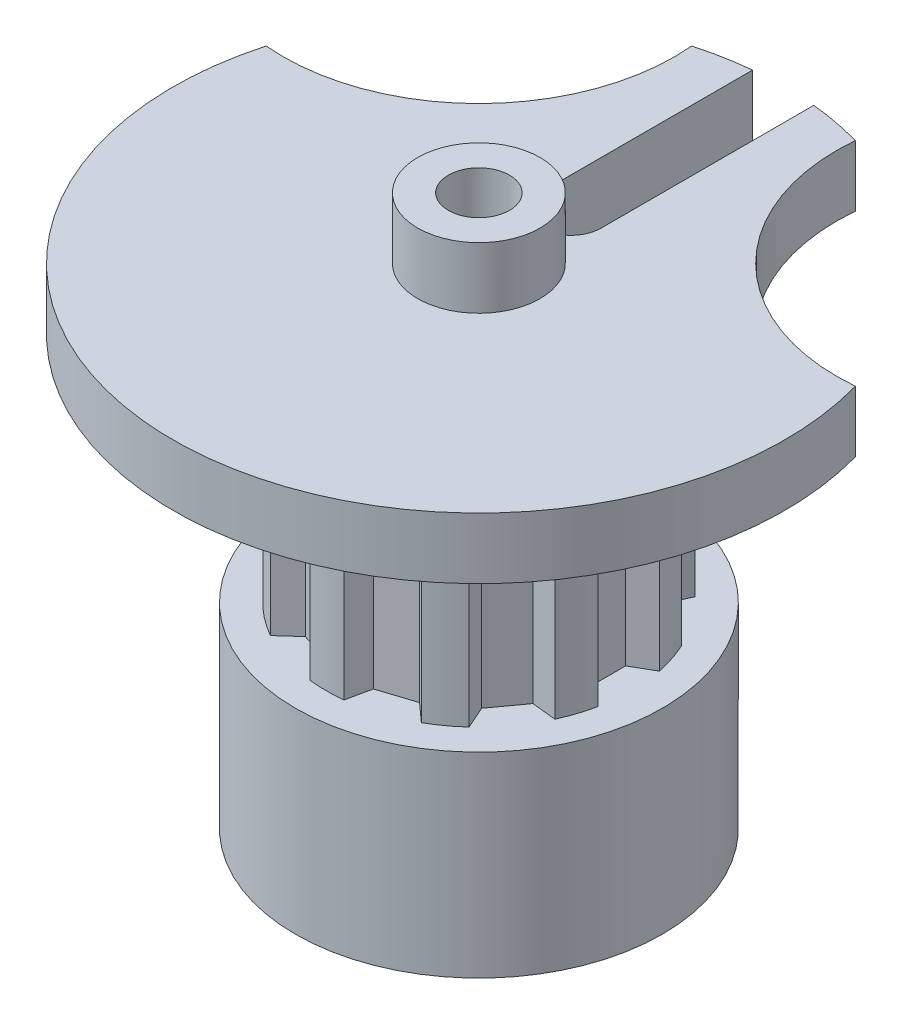
SolidWorks part; units mm, degrees
material "AISI 304"
ref_plane "Front" through (0, 0, 0) normal (0, 0, 1) x (1, 0, 0)
ref_plane "Top" through (0, 0, 0) normal (0, 1, 0) x (1, 0, 0)
ref_plane "Right" through (0, 0, 0) normal (1, 0, 0) x (0, 0, -1)
sketch "Sketch1" plane through (0, 0, 0) normal (0, 1, 0) x (1, 0, 0)
  circle A0 centre (0, 0) radius 25
  circle A1 centre (0, 0) radius 2.5
  dimension "D1" = 50
  dimension "D2" = 5
extrude "Boss-Extrude1" add sketch "Sketch1" along normal blind 5
sketch "Sketch2" plane through (0, 5, 0) normal (0, 1, 0) x (1, 0, 0)
  line L0 (-2.5, 24.8747) -> (-2.5, 7.5)
  line L1 (2.5, 7.5) -> (2.5, 24.8747)
  line L2 (-22.6274, 22.6274) -> (22.6274, 22.6274) construction
  line L3 (22.6274, 22.6274) -> (0, 0) construction
  line L4 (0, 0) -> (0, 22.6274) construction
  circle A2 centre (0, 0) radius 25 construction
  arc A3 (-2.5, 7.5) -> (2.5, 7.5) centre (0, 7.5) ccw
  circle A5 centre (22.6274, 22.6274) radius 16
  circle A6 centre (-22.6274, 22.6274) radius 16
  arc A7 (-2.5, 24.8747) -> (2.5, 24.8747) centre (0, 0) cw
  dimension "D3" = 45
  dimension "D2" = 32
  dimension "D1" = 5
  dimension "D4" = 7.5
  dimension "D5" = 32
extrude "Cut-Extrude1" cut sketch "Sketch2" against normal through all
sketch "Sketch3" plane through (0, 5, 0) normal (0, 1, 0) x (1, 0, 0)
  circle A0 centre (0, 0) radius 5
  circle A1 centre (0, 0) radius 2.5
  circle A2 centre (0, 0) radius 2.5 construction
  arc A3 (-2.5, 7.5) -> (2.5, 7.5) centre (0, 7.5) ccw construction
extrude "Boss-Extrude2" add sketch "Sketch3" along normal blind 5
sketch "Sketch4" plane through (0, 0, 0) normal (0, -1, 0) x (1, 0, 0)
  circle A0 centre (0, 0) radius 15
  circle A1 centre (0, 0) radius 2.5
  circle A2 centre (0, 0) radius 2.5 construction
  dimension "D1" = 30
extrude "Boss-Extrude3" add sketch "Sketch4" along normal blind 35
sketch "Sketch5" plane through (0, 0, 0) normal (0, 1, 0) x (1, 0, 0)
  line L33 (-10.5, 1.5) -> (-10.5, -1.5)
  line L34 (-10.5, -1.5) -> (-12.2458, -2.508)
  line L35 (-10.5, 1.5) -> (-12.2458, 2.508)
  line L36 (-7.613, 7.3853) -> (-9.3764, 4.9582)
  line L37 (-7.613, 7.3853) -> (-8.4329, 9.2269)
  line L38 (-9.3764, 4.9582) -> (-11.3812, 5.1689)
  line L39 (-1.8181, 10.4496) -> (-4.6713, 9.5226)
  line L40 (-1.8181, 10.4496) -> (-1.399, 12.4215)
  line L41 (-4.6713, 9.5226) -> (-6.1694, 10.8715)
  line L42 (4.6713, 9.5226) -> (1.8181, 10.4496)
  line L43 (4.6713, 9.5226) -> (6.1694, 10.8715)
  line L44 (1.8181, 10.4496) -> (1.399, 12.4215)
  line L45 (9.3764, 4.9582) -> (7.613, 7.3853)
  line L46 (9.3764, 4.9582) -> (11.3812, 5.1689)
  line L47 (7.613, 7.3853) -> (8.4329, 9.2269)
  line L48 (10.5, -1.5) -> (10.5, 1.5)
  line L49 (10.5, -1.5) -> (12.2458, -2.508)
  line L50 (10.5, 1.5) -> (12.2458, 2.508)
  line L51 (7.613, -7.3853) -> (9.3764, -4.9582)
  line L52 (7.613, -7.3853) -> (8.4329, -9.2269)
  line L53 (9.3764, -4.9582) -> (11.3812, -5.1689)
  line L54 (1.8181, -10.4496) -> (4.6713, -9.5226)
  line L55 (1.8181, -10.4496) -> (1.399, -12.4215)
  line L56 (4.6713, -9.5226) -> (6.1694, -10.8715)
  line L57 (-4.6713, -9.5226) -> (-1.8181, -10.4496)
  line L58 (-4.6713, -9.5226) -> (-6.1694, -10.8715)
  line L59 (-1.8181, -10.4496) -> (-1.399, -12.4215)
  line L60 (-9.3764, -4.9582) -> (-7.613, -7.3853)
  line L61 (-9.3764, -4.9582) -> (-11.3812, -5.1689)
  line L62 (-7.613, -7.3853) -> (-8.4329, -9.2269)
  circle A12 centre (0, 0) radius 15
  arc A13 (-11.3812, 5.1689) -> (-12.2458, 2.508) centre (0, 0) ccw
  circle A14 centre (0, 0) radius 15 construction
  arc A15 (-12.2458, -2.508) -> (-11.3812, -5.1689) centre (0, 0) ccw
  arc A16 (-8.4329, -9.2269) -> (-6.1694, -10.8715) centre (0, 0) ccw
  arc A17 (-1.399, -12.4215) -> (1.399, -12.4215) centre (0, 0) ccw
  arc A18 (6.1694, -10.8715) -> (8.4329, -9.2269) centre (0, 0) ccw
  arc A19 (11.3812, -5.1689) -> (12.2458, -2.508) centre (0, 0) ccw
  arc A20 (12.2458, 2.508) -> (11.3812, 5.1689) centre (0, 0) ccw
  arc A21 (8.4329, 9.2269) -> (6.1694, 10.8715) centre (0, 0) ccw
  arc A22 (1.399, 12.4215) -> (-1.399, 12.4215) centre (0, 0) ccw
  arc A23 (-6.1694, 10.8715) -> (-8.4329, 9.2269) centre (0, 0) ccw
  point P9 (-10.5, 0)
  point P50 (0, 0)
  dimension "D3" = 25
  dimension "D1" = 60
  dimension "D2" = 10.5
  dimension "D4" = 3
extrude "Cut-Extrude2" cut sketch "Sketch5" against normal blind 14 from offset 5
